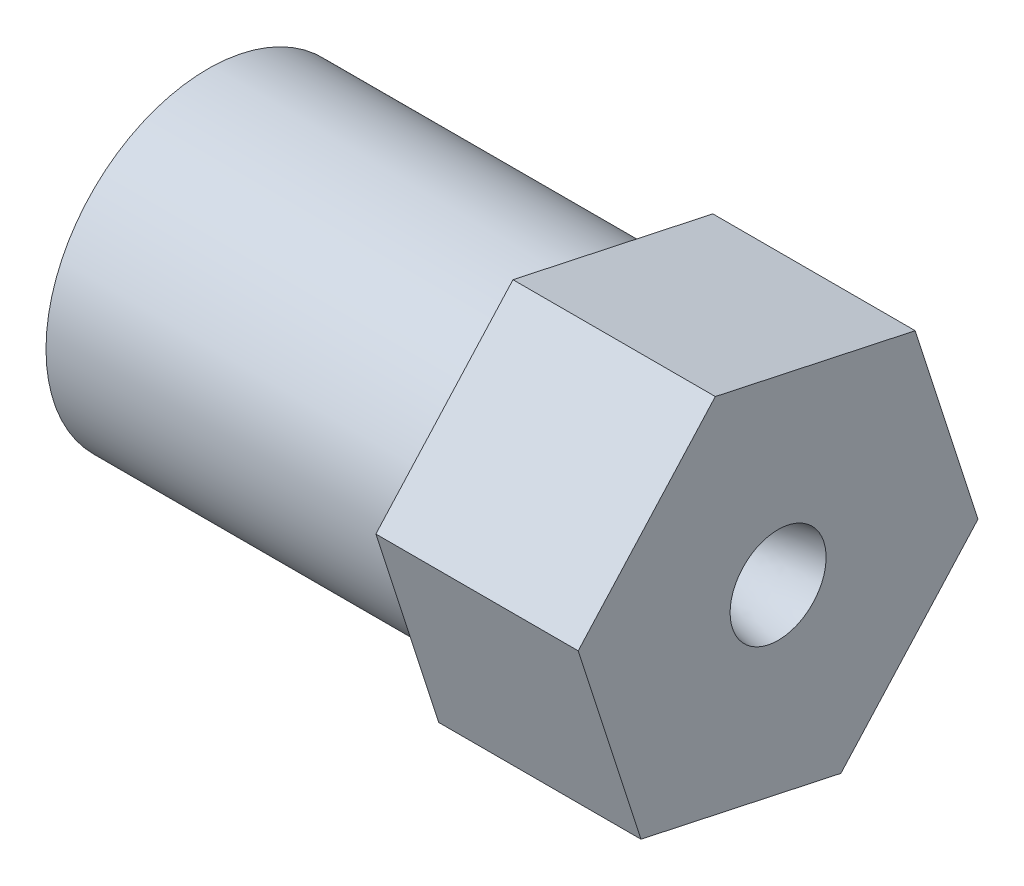
SolidWorks part; units mm, degrees
ref_plane "Front Plane" through (0, 0, 0) normal (0, 0, 1) x (1, 0, 0)
ref_plane "Top Plane" through (0, 0, 0) normal (0, 1, 0) x (1, 0, 0)
ref_plane "Right Plane" through (0, 0, 0) normal (1, 0, 0) x (0, 0, -1)
sketch "Sketch1" plane through (0, 0, 0) normal (0, 0, 1) x (1, 0, 0)
  line L0 (0, 0) -> (4.0383, 0) construction
  line L1 (0.278, 2.081) -> (4.0383, 3.4497) construction
  line L2 (-2.1553, 2.9247) -> (-2.7456, 3.5151)
  line L3 (-31.75, 4.445) -> (-31.75, 10.16) construction
  line L4 (-4.9907, 4.445) -> (-31.75, 4.445) construction
  line L5 (-31.75, 10.16) -> (-8.6617, 10.16)
  line L6 (4.0383, 10.16) -> (4.0383, 3.0139)
  line L7 (4.0383, 3.0139) -> (12.98, 4.2706) construction
  line L8 (-8.6617, 10.16) -> (4.0383, 10.16)
  line L9 (-4.9907, 4.445) -> (-13.462, 4.445)
  line L10 (-19.939, 5.461) -> (-19.939, 6.8199)
  line L11 (-20.066, 6.9469) -> (-24.892, 6.9469)
  line L12 (-24.892, 6.9469) -> (-24.892, 7.8994)
  line L13 (-25.019, 8.0264) -> (-31.115, 8.0264)
  line L14 (-31.75, 10.16) -> (-31.75, 8.6614)
  line L15 (0, 0) -> (-31.75, 0) construction
  line L16 (-13.462, 4.445) -> (-13.462, 4.699)
  line L17 (-13.589, 4.826) -> (-19.304, 4.826)
  arc A0 (-2.1553, 2.9247) -> (0, 2.032) centre (0, 5.08) ccw
  arc A1 (0, 2.032) -> (0.278, 2.081) centre (0, 2.8448) ccw
  arc A2 (-2.7456, 3.5151) -> (-4.9907, 4.445) centre (-4.9907, 1.27) ccw
  arc A3 (-31.115, 8.0264) -> (-31.75, 8.6614) centre (-31.115, 8.6614) cw
  arc A4 (-19.304, 4.826) -> (-19.939, 5.461) centre (-19.304, 5.461) cw
  arc A5 (-13.462, 4.699) -> (-13.589, 4.826) centre (-13.589, 4.699) ccw
  arc A6 (-19.939, 6.8199) -> (-20.066, 6.9469) centre (-20.066, 6.8199) ccw
  arc A7 (-24.892, 7.8994) -> (-25.019, 8.0264) centre (-25.019, 7.8994) ccw
  parabola Q0 (4.0383, 3.0139) -> (0.278, 2.081) focus (3.3776, -6.4351) apex (0.278, 2.081)
  point P30 (-31.75, 8.0264)
  point P39 (-24.892, 8.0264)
  dimension "D3" = 3.048
  dimension "D4" = 0.8128
  dimension "D11" = 3.175
  dimension "D12" = 8
  dimension "D14" = 6.9469
  dimension "D20" = 0.635
  dimension "D21" = 0.127
  dimension "D2" = 4.0383
  dimension "D5" = 3.0139
  dimension "D6" = 20
  dimension "D7" = 45
  dimension "D8" = 8.0264
  dimension "D9" = 31.75
  dimension "D10" = 10.16
  dimension "D13" = 12.7
  dimension "D15" = 4.445
  dimension "D16" = 6.858
  dimension "D17" = 11.811
  dimension "D18" = 18.288
  dimension "D19" = 4.826
  dimension "D22" = 2.032
revolve "Revolve1" add sketch "Sketch1" angle 360 about L0
sketch "Sketch4" plane through (4.0383, 0, 0) normal (1, 0, 0) x (0, 0, -1)
  line L1 (3.9404, -12.2116) -> (12.5458, -2.6933)
  line L2 (12.5458, -2.6933) -> (8.6054, 9.5183)
  line L3 (8.6054, 9.5183) -> (-3.9404, 12.2116)
  line L4 (-3.9404, 12.2116) -> (-12.5458, 2.6933)
  line L5 (-12.5458, 2.6933) -> (-8.6054, -9.5183)
  line L6 (-8.6054, -9.5183) -> (3.9404, -12.2116)
  circle A0 centre (0, 0) radius 10.16
  circle A1 centre (0, 0) radius 10.16 construction
  circle A2 centre (0, 0) radius 11.1125 construction
  circle M1 centre (0, 0) radius 10.16
  dimension "D1" = 22.225
extrude "Boss-Extrude1" add sketch "Sketch4" against normal blind 12.7 contours L4 L5 M1 | L3 L4 M1 | L2 L3 M1 | L1 L2 M1 | L6 L1 M1 | L5 L6 M1
fillet "Fillet1" radius 0.635 1 edges at (-8.6617, 0, -10.16)
equation "\"D3@Sketch1\" = 1.5 * \"D22@Sketch1\""
equation "\"D4@Sketch1\"  = .4 * \"D22@Sketch1\""
equation "\"D5@Sketch1\"=\"D22@Sketch1\" * ( \"er\") ^ .5"
equation "\"er\"= 2.2"
